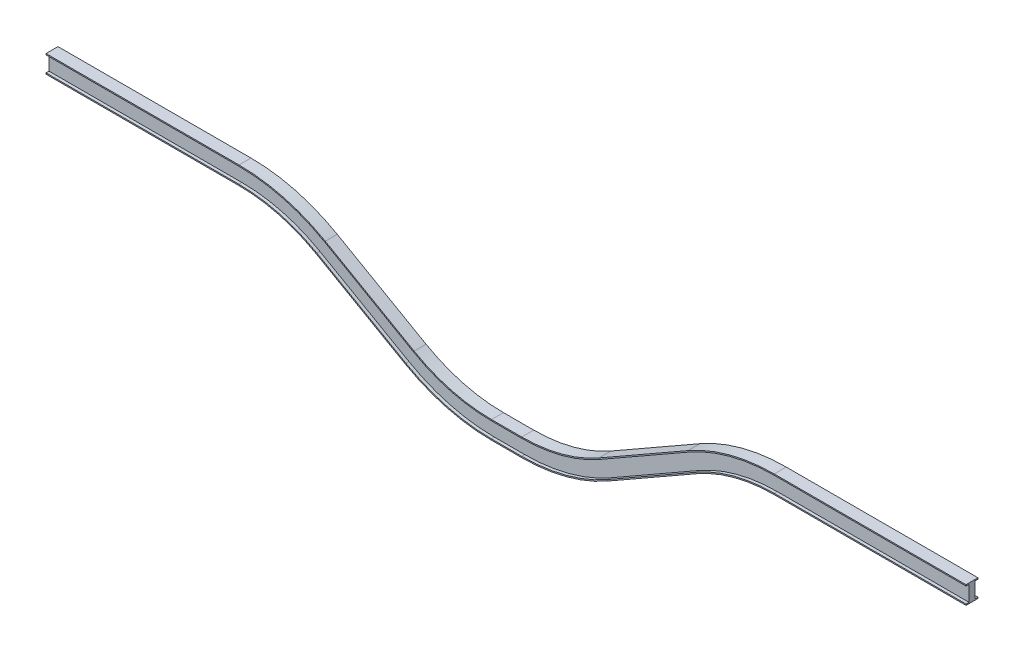
SolidWorks part; units mm, degrees
ref_plane "Alzado" through (0, 0, 0) normal (0, 0, 1) x (1, 0, 0)
ref_plane "Planta" through (0, 0, 0) normal (0, 1, 0) x (1, 0, 0)
ref_plane "Vista lateral" through (0, 0, 0) normal (1, 0, 0) x (0, 0, -1)
sketch "Croquis2" plane through (0, 0, 0) normal (1, 0, 0) x (0, 0, -1)
  line L1 (0, 0) -> (101.6, 0)
  line L2 (0, 0) -> (0, -152.4)
  line L3 (0, -152.4) -> (101.6, -152.4)
  line L4 (101.6, 0) -> (101.6, -152.4)
  dimension "D1" = 101.6
  dimension "D2" = 152.4
extrude "Saliente-Extruir1" add sketch "Croquis2" along normal blind 10
sketch3d "Croquis3D1"
  line L0 (10, -76.2, 0) -> (10, -76.2, -101.6) construction
  line L1 (10, 0, 0) -> (10, -152.4, 0) construction
  line L2 (10, -152.4, -101.6) -> (10, 0, -101.6) construction
  line L3 (10, -76.2, -50.8) -> (1638.2098, -76.2, -50.8)
  line L4 (2010, -76.2, -50.8) -> (3410, -76.2, -50.8) construction
  line L5 (3410, -76.2, -50.8) -> (3410, -876.2, -50.8) construction
  line L6 (3087.1957, -691.7404, -50.8) -> (2332.8043, -260.6596, -50.8)
  line L7 (3781.7902, -876.2, -50.8) -> (4038.2098, -876.2, -50.8)
  line L8 (4410, -876.2, -50.8) -> (4410, -76.2, -50.8) construction
  line L9 (4410, -76.2, -50.8) -> (5810, -76.2, -50.8) construction
  line L10 (5487.1957, -260.6596, -50.8) -> (4732.8043, -691.7404, -50.8)
  line L11 (6181.7902, -76.2, -50.8) -> (7810, -76.2, -50.8)
  arc A0 (5487.1957, -260.6596, -50.8) -> (6181.7902, -76.2, -50.8) centre (6181.7902, -1476.2, -50.8) ccw
  arc A1 (1638.2098, -76.2, -50.8) -> (2332.8043, -260.6596, -50.8) centre (1638.2098, -1476.2, -50.8) ccw
  arc A2 (4038.2098, -876.2, -50.8) -> (4732.8043, -691.7404, -50.8) centre (4038.2098, 523.8, -50.8) ccw
  arc A3 (3087.1957, -691.7404, -50.8) -> (3781.7902, -876.2, -50.8) centre (3781.7902, 523.8, -50.8) ccw
  point P16 (5810, -76.2, -50.8)
  point P18 (6181.7902, -1476.2, -1450.8)
  point P21 (2010, -76.2, -50.8)
  point P23 (1638.2098, -1476.2, -1450.8)
  point P26 (4410, -876.2, -50.8)
  point P28 (4038.2098, 523.8, 1349.2)
  point P31 (3410, -876.2, -50.8)
  point P33 (3781.7902, 523.8, 1349.2)
  dimension "D8" = 1400
  dimension "D9" = 1400
  dimension "D1" = 2000
  dimension "D2" = 1400
  dimension "D3" = 800
  dimension "D4" = 1000
  dimension "D5" = 800
  dimension "D6" = 1400
  dimension "D7" = 2000
sketch "Croquis4" plane through (10, 0, 0) normal (1, 0, 0) x (0, 0, -1)
  line L1 (0, 0) -> (101.6, 0)
  line L2 (0, 0) -> (0, -152.4)
  line L3 (0, -152.4) -> (101.6, -152.4)
  line L4 (101.6, 0) -> (101.6, -152.4)
sweep "Barrer1" add profiles "Croquis4" path "Croquis3D1"
sketch "Croquis6" plane through (0, 0, 0) normal (0, 0, 1) x (1, 0, 0)
  line L0 (0, 0) -> (1638.2098, 0) construction
  line L1 (1638.2098, 0) -> (0, 0) construction
  line L2 (2370.6101, -194.4995) -> (3125.0015, -625.5803) construction
  line L3 (3781.7902, -800) -> (4038.2098, -800) construction
  line L4 (4694.9985, -625.5803) -> (5449.3899, -194.4995) construction
  line L5 (6181.7902, 0) -> (7810, 0) construction
  line L6 (7810, 0) -> (7810, -10) construction
  line L7 (7810, -152.4) -> (6181.7902, -152.4) construction
  line L8 (5525.0015, -326.8197) -> (4770.6101, -757.9005) construction
  line L9 (4038.2098, -952.4) -> (3781.7902, -952.4) construction
  line L10 (3781.7902, -952.4) -> (4038.2098, -952.4) construction
  line L11 (3049.3899, -757.9005) -> (2294.9985, -326.8197) construction
  line L12 (1638.2098, -152.4) -> (0, -152.4) construction
  line L13 (0, 0) -> (0, -10) construction
  line L14 (10, -10) -> (10, -142.4) construction
  line L15 (1638.2098, -142.4) -> (10, -142.4)
  line L16 (3054.3513, -749.2181) -> (2299.9599, -318.1373)
  line L17 (4038.2098, -942.4) -> (3781.7902, -942.4)
  line L18 (5520.0401, -318.1373) -> (4765.6487, -749.2181)
  line L19 (7800, -142.4) -> (6181.7902, -142.4)
  line L20 (7800, -10) -> (7800, -142.4) construction
  line L21 (6181.7902, -10) -> (7800, -10)
  line L22 (4699.9599, -634.2627) -> (5454.3513, -203.1819)
  line L23 (3781.7902, -810) -> (4038.2098, -810)
  line L24 (2365.6487, -203.1819) -> (3120.0401, -634.2627)
  line L25 (10, -10) -> (1638.2098, -10)
  line L26 (10, -10) -> (0, -10)
  line L27 (10, -142.4) -> (0, -142.4)
  line L28 (0, -142.4) -> (0, -152.4) construction
  line L29 (0, 0) -> (0, -152.4) construction
  line L30 (0, -10) -> (0, -142.4)
  line L31 (7800, -10) -> (7810, -10)
  line L32 (7800, -142.4) -> (7810, -142.4)
  line L33 (7810, -142.4) -> (7810, -152.4) construction
  line L34 (7810, 0) -> (7810, -152.4) construction
  line L35 (7810, -142.4) -> (7810, -10)
  arc A0 (2370.6101, -194.4995) -> (1638.2098, 0) centre (1638.2098, -1476.2) ccw construction
  arc A1 (1638.2098, 0) -> (2370.6101, -194.4995) centre (1638.2098, -1476.2) cw construction
  arc A2 (3125.0015, -625.5803) -> (3781.7902, -800) centre (3781.7902, 523.8) ccw construction
  arc A3 (4038.2098, -800) -> (4694.9985, -625.5803) centre (4038.2098, 523.8) ccw construction
  arc A4 (5449.3899, -194.4995) -> (6181.7902, 0) centre (6181.7902, -1476.2) cw construction
  arc A5 (6181.7902, -152.4) -> (5525.0015, -326.8197) centre (6181.7902, -1476.2) ccw construction
  arc A6 (4770.6101, -757.9005) -> (4038.2098, -952.4) centre (4038.2098, 523.8) cw construction
  arc A7 (3049.3899, -757.9005) -> (3781.7902, -952.4) centre (3781.7902, 523.8) ccw construction
  arc A8 (3781.7902, -952.4) -> (3049.3899, -757.9005) centre (3781.7902, 523.8) cw construction
  arc A9 (2294.9985, -326.8197) -> (1638.2098, -152.4) centre (1638.2098, -1476.2) ccw construction
  arc A10 (2299.9599, -318.1373) -> (1638.2098, -142.4) centre (1638.2098, -1476.2) ccw
  arc A11 (3781.7902, -942.4) -> (3054.3513, -749.2181) centre (3781.7902, 523.8) cw
  arc A12 (4765.6487, -749.2181) -> (4038.2098, -942.4) centre (4038.2098, 523.8) cw
  arc A13 (6181.7902, -142.4) -> (5520.0401, -318.1373) centre (6181.7902, -1476.2) ccw
  arc A14 (5454.3513, -203.1819) -> (6181.7902, -10) centre (6181.7902, -1476.2) cw
  arc A15 (4038.2098, -810) -> (4699.9599, -634.2627) centre (4038.2098, 523.8) ccw
  arc A16 (3120.0401, -634.2627) -> (3781.7902, -810) centre (3781.7902, 523.8) ccw
  arc A17 (1638.2098, -10) -> (2365.6487, -203.1819) centre (1638.2098, -1476.2) cw
  dimension "D1" = 10
extrude "Cortar-Extruir2" cut sketch "Croquis6" against normal blind 25.4
sketch "Croquis7" plane through (0, 0, -101.6) normal (0, 0, -1) x (-1, 0, 0)
  line L0 (0, -10) -> (-1638.2098, -10)
  line L1 (-2365.6487, -203.1819) -> (-3120.0401, -634.2627)
  line L2 (-3781.7902, -952.4) -> (-3781.7902, -800) construction
  line L3 (-3781.7902, -810) -> (-4038.2098, -810)
  line L4 (-4699.9599, -634.2627) -> (-5454.3513, -203.1819)
  line L5 (-6181.7902, -10) -> (-7810, -10)
  line L6 (-7810, -10) -> (-7810, -142.4)
  line L7 (-7810, -142.4) -> (-6181.7902, -142.4)
  line L8 (-5520.0401, -318.1373) -> (-4765.6487, -749.2181)
  line L9 (-4038.2098, -942.4) -> (-3781.7902, -942.4)
  line L10 (-3054.3513, -749.2181) -> (-2299.9599, -318.1373)
  line L11 (-1638.2098, -142.4) -> (0, -142.4)
  line L12 (0, -142.4) -> (0, -10)
  arc A0 (-1638.2098, -10) -> (-2365.6487, -203.1819) centre (-1638.2098, -1476.2) ccw
  arc A1 (-3120.0401, -634.2627) -> (-3781.7902, -810) centre (-3781.7902, 523.8) cw
  arc A2 (-3781.7902, -810) -> (-3120.0401, -634.2627) centre (-3781.7902, 523.8) ccw construction
  arc A3 (-4038.2098, -810) -> (-4699.9599, -634.2627) centre (-4038.2098, 523.8) cw
  arc A4 (-5454.3513, -203.1819) -> (-6181.7902, -10) centre (-6181.7902, -1476.2) ccw
  arc A5 (-6181.7902, -142.4) -> (-5520.0401, -318.1373) centre (-6181.7902, -1476.2) cw
  arc A6 (-4765.6487, -749.2181) -> (-4038.2098, -942.4) centre (-4038.2098, 523.8) ccw
  arc A7 (-3781.7902, -942.4) -> (-3054.3513, -749.2181) centre (-3781.7902, 523.8) ccw
  arc A8 (-2299.9599, -318.1373) -> (-1638.2098, -142.4) centre (-1638.2098, -1476.2) cw
  arc A9 (-1638.2098, -142.4) -> (-2299.9599, -318.1373) centre (-1638.2098, -1476.2) ccw construction
extrude "Cortar-Extruir3" cut sketch "Croquis7" against normal blind 25.4
